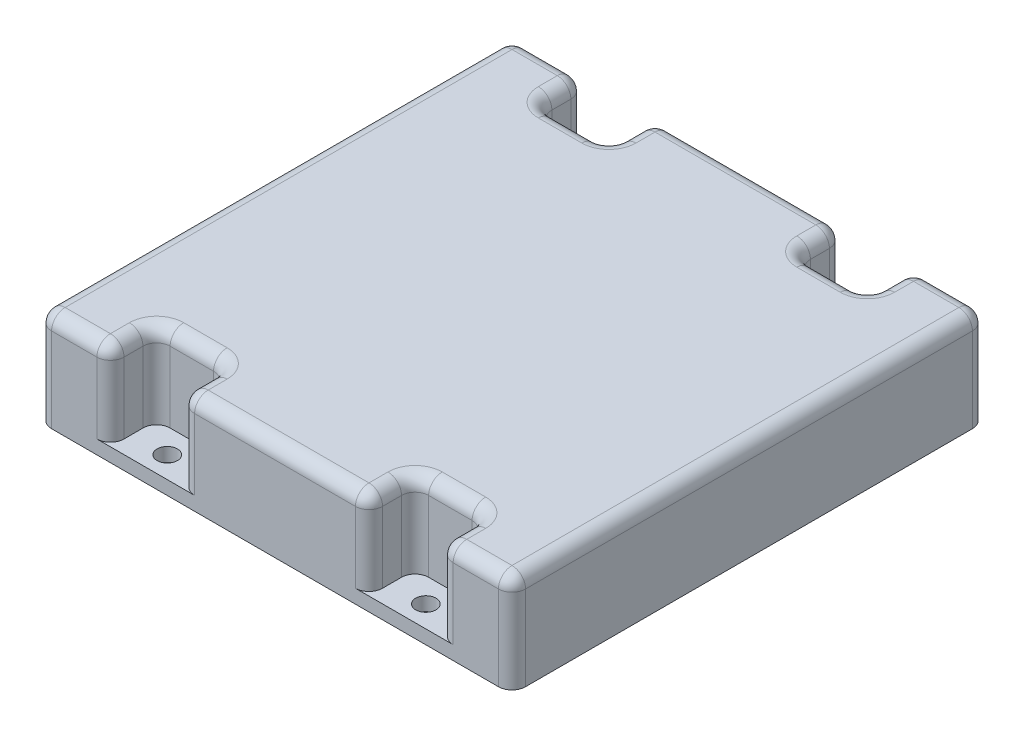
SolidWorks part; units mm, degrees
ref_plane "Front Plane" through (0, 0, 0) normal (0, 0, 1) x (1, 0, 0)
ref_plane "Top Plane" through (0, 0, 0) normal (0, 1, 0) x (1, 0, 0)
ref_plane "Right Plane" through (0, 0, 0) normal (1, 0, 0) x (0, 0, -1)
sketch "Sketch1" plane through (0, 0, 0) normal (0, 1, 0) x (1, 0, 0)
  line L1 (-69.85, -69.85) -> (69.85, -69.85)
  line L2 (-69.85, -69.85) -> (-69.85, 69.85)
  line L3 (-69.85, 69.85) -> (69.85, 69.85)
  line L4 (69.85, -69.85) -> (69.85, 69.85)
  line L5 (-69.85, -69.85) -> (69.85, 69.85) construction
  line L6 (-69.85, 69.85) -> (69.85, -69.85) construction
  point P0 (0, 0)
  dimension "D1" = 139.7
  dimension "D2" = 139.7
extrude "Boss-Extrude1" add sketch "Sketch1" along normal blind 4.064
sketch "Sketch2" plane through (0, 4.064, 0) normal (0, 1, 0) x (1, 0, 0)
  line L0 (-48.5013, 56.261) -> (-38.1, 69.85) construction
  line L1 (69.85, 69.85) -> (-69.85, 69.85) construction
  line L2 (-38.1, 69.85) -> (-27.6987, 56.261) construction
  line L3 (27.6987, 56.261) -> (38.1, 69.85) construction
  line L4 (27.6987, 69.85) -> (-27.6987, 69.85)
  line L6 (-48.5013, 69.85) -> (-48.5013, 56.261)
  line L7 (-48.5013, 56.261) -> (-27.6987, 56.261)
  line L8 (69.85, -69.85) -> (69.85, 69.85)
  line L9 (69.85, 69.85) -> (-69.85, 69.85)
  line L10 (-69.85, 69.85) -> (-69.85, -69.85)
  line L11 (-69.85, -69.85) -> (69.85, -69.85)
  line L12 (69.85, -69.85) -> (69.85, 69.85)
  line L14 (-69.85, 69.85) -> (-69.85, -69.85)
  line L16 (-27.6987, 69.85) -> (-27.6987, 56.261)
  line L17 (69.85, 69.85) -> (48.5013, 69.85)
  line L18 (27.6987, 69.85) -> (27.6987, 56.261)
  line L19 (27.6987, 56.261) -> (48.5013, 56.261)
  line L20 (48.5013, 69.85) -> (48.5013, 56.261)
  line L22 (27.6987, -69.85) -> (27.6987, -56.261)
  line L23 (27.6987, -56.261) -> (48.5013, -56.261)
  line L24 (48.5013, -69.85) -> (48.5013, -56.261)
  line L26 (-27.6987, -69.85) -> (-27.6987, -56.261)
  line L27 (-27.6987, -56.261) -> (-48.5013, -56.261)
  line L28 (-48.5013, -69.85) -> (-48.5013, -56.261)
  line L29 (-48.5013, 69.85) -> (-69.85, 69.85)
  line L30 (-48.5013, -69.85) -> (-69.85, -69.85)
  line L31 (-27.6987, -69.85) -> (27.6987, -69.85)
  line L32 (48.5013, -69.85) -> (69.85, -69.85)
  line L33 (38.1, 69.85) -> (48.5013, 56.261) construction
  line L34 (27.6987, -56.261) -> (38.1, -69.85) construction
  line L35 (-69.85, -69.85) -> (69.85, -69.85) construction
  line L36 (38.1, -69.85) -> (48.5013, -56.261) construction
  line L37 (-48.5013, -56.261) -> (-38.1, -69.85) construction
  line L38 (-38.1, -69.85) -> (-27.6987, -56.261) construction
  dimension "D2" = 31.75
  dimension "D3" = 31.75
  dimension "D4" = 31.75
  dimension "D5" = 31.75
  dimension "D6" = 20.8026
  dimension "D7" = 13.589
  dimension "D1" = 0
extrude "Boss-Extrude2" add sketch "Sketch2" along normal blind 24.892
fillet "Fillet1" radius 4 20 edges at (69.85, 14.478, -69.85) (48.5013, 16.51, -69.85) (48.5013, 16.51, -56.261) (27.6987, 16.51, -56.261) (27.6987, 16.51, -69.85) (-27.6987, 16.51, -69.85) (-27.6987, 16.51, -56.261) (-48.5013, 16.51, -56.261) (-48.5013, 16.51, -69.85) (-69.85, 14.478, -69.85) (-69.85, 14.478, 69.85) (-48.5013, 16.51, 69.85) (-48.5013, 16.51, 56.261) (-27.6987, 16.51, 56.261) (-27.6987, 16.51, 69.85) (48.5013, 16.51, 69.85) (48.5013, 16.51, 56.261) (27.6987, 16.51, 56.261) (27.6987, 16.51, 69.85) (69.85, 14.478, 69.85)
fillet "Fillet2" radius 4 40 edges at (-68.6784, 28.956, -68.6784) (-59.1756, 28.956, -69.85) (-49.6729, 28.956, -68.6784) (-48.5013, 28.956, -63.0555) (-47.3297, 28.956, -57.4326) (-38.1, 28.956, -56.261) (-28.8703, 28.956, -57.4326) (-27.6987, 28.956, -63.0555) (-26.5271, 28.956, -68.6784) (0, 28.956, -69.85) (26.5271, 28.956, -68.6784) (27.6987, 28.956, -63.0555) (28.8703, 28.956, -57.4326) (38.1, 28.956, -56.261) (47.3297, 28.956, -57.4326) (48.5013, 28.956, -63.0555) (49.6729, 28.956, -68.6784) (59.1756, 28.956, -69.85) (68.6784, 28.956, -68.6784) (69.85, 28.956, 0) (68.6784, 28.956, 68.6784) (59.1756, 28.956, 69.85) (49.6729, 28.956, 68.6784) (48.5013, 28.956, 63.0555) (47.3297, 28.956, 57.4326) (38.1, 28.956, 56.261) (28.8703, 28.956, 57.4326) (27.6987, 28.956, 63.0555) (26.5271, 28.956, 68.6784) (0, 28.956, 69.85) (-26.5271, 28.956, 68.6784) (-27.6987, 28.956, 63.0555) (-28.8703, 28.956, 57.4326) (-38.1, 28.956, 56.261) (-47.3297, 28.956, 57.4326) (-48.5013, 28.956, 63.0555) (-49.6729, 28.956, 68.6784) (-59.1756, 28.956, 69.85) (-68.6784, 28.956, 68.6784) (-69.85, 28.956, 0)
hole_wizard "Ø6.0 (6) Diameter Hole1" positions "Sketch3" profile "Sketch4" hole size "Ø6.0" standard "ANSI Metric"
sketch "Sketch3" plane through (0, 4.064, 0) normal (0, 1, 0) x (1, 0, 0)
  line L1 (-38.1, 63.5) -> (38.1, 63.5) construction
  line L2 (-38.1, 63.5) -> (-38.1, -63.5) construction
  line L3 (-38.1, -63.5) -> (38.1, -63.5) construction
  line L4 (38.1, 63.5) -> (38.1, -63.5) construction
  line L5 (-38.1, 63.5) -> (38.1, -63.5) construction
  point P0 (-38.1, 63.5)
  point P2 (38.1, 63.5)
  point P4 (38.1, -63.5)
  point P6 (-38.1, -63.5)
  dimension "D1" = 127
  dimension "D2" = 76.2
sketch "Sketch4" plane through (-38.1, 4.064, -63.5) normal (1, 0, 0) x (0, 0, 1)
  line L0 (0, 0) -> (0, 20.5526)
  line L1 (0, 20.5526) -> (3, 18.75)
  line L2 (3, 18.75) -> (3, 0)
  line L5 (3, 0) -> (0, 0)
  line L10 (0, 20.5526) -> (-3, 18.75) construction
  line L11 (0, -6.35) -> (0, 107.95) construction
  dimension "Hole Dia." = 6
  dimension "Hole Depth" = 18.75
  dimension "Drill Angle" = 118
